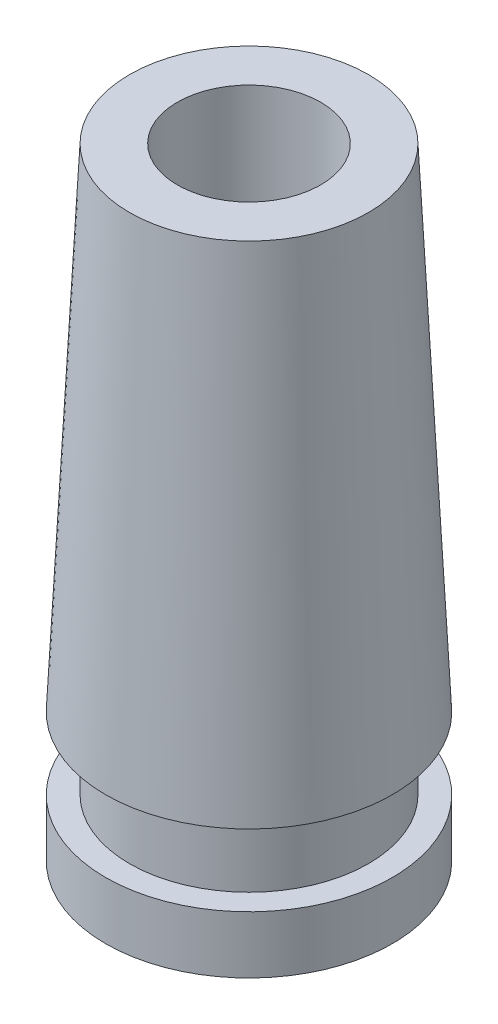
SolidWorks part; units mm, degrees
ref_plane "Plan de face" through (0, 0, 0) normal (0, 0, 1) x (1, 0, 0)
ref_plane "Plan de dessus" through (0, 0, 0) normal (0, 1, 0) x (1, 0, 0)
ref_plane "Plan de droite" through (0, 0, 0) normal (1, 0, 0) x (0, 0, -1)
sketch "Esquisse1" plane through (0, 0, 0) normal (0, 0, 1) x (1, 0, 0)
  line L0 (0, 0) -> (0, 41.8353) construction
  line L1 (-1.5, 0) -> (-3, 0)
  line L2 (-3, 0) -> (-3, 1.2)
  line L3 (-3, 1.2) -> (-2.5, 1.2)
  line L4 (-2.5, 1.2) -> (-2.5, 2.7)
  line L5 (-2.5, 2.7) -> (-3, 2.7)
  line L7 (-3, 2.7) -> (-2.5, 13)
  line L8 (-2.5, 13) -> (-1.5, 13)
  line L9 (-1.5, 13) -> (-1.5, 0)
  point P9 (0, 0)
  point P13 (0, 0)
  dimension "D1" = 3
  dimension "D2" = 6
  dimension "D3" = 5
  dimension "D4" = 6
  dimension "D5" = 5
  dimension "D6" = 13
  dimension "D7" = 1.2
  dimension "D8" = 1.5
revolve "Révolution1" add sketch "Esquisse1" angle 360 about L0
